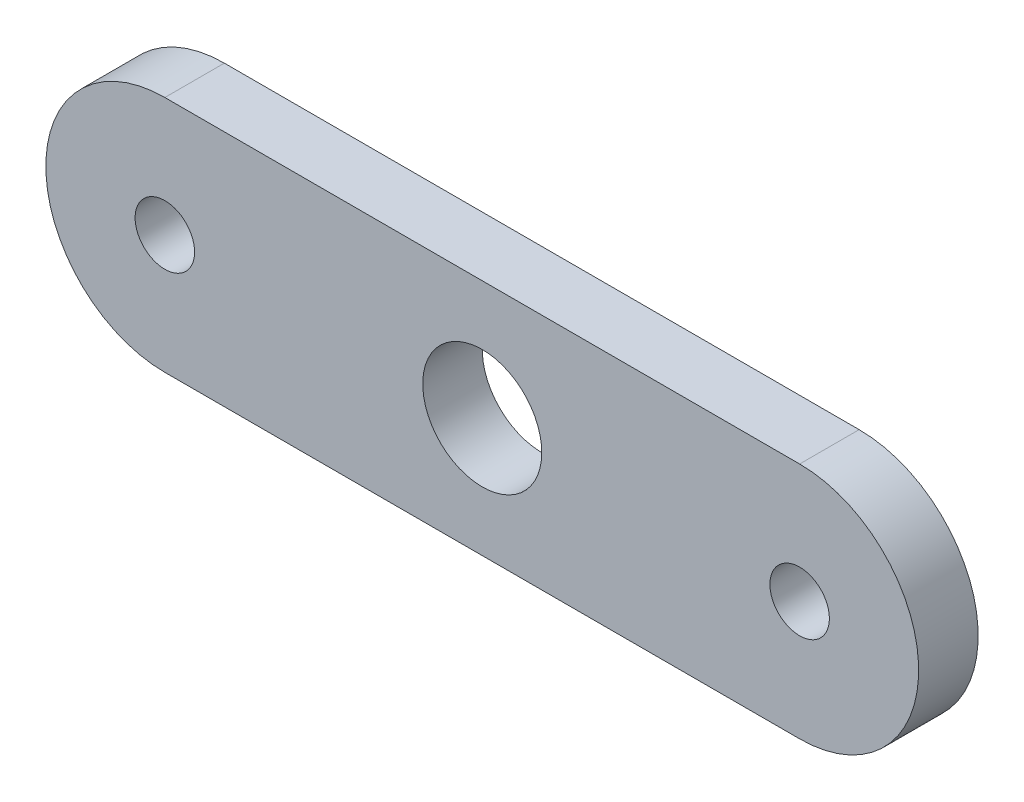
SolidWorks part; units mm, degrees
ref_plane "Front Plane" through (0, 0, 0) normal (0, 0, 1) x (1, 0, 0)
ref_plane "Top Plane" through (0, 0, 0) normal (0, 1, 0) x (1, 0, 0)
ref_plane "Right Plane" through (0, 0, 0) normal (1, 0, 0) x (0, 0, -1)
sketch "Sketch1" plane through (0, 0, 0) normal (0, 0, 1) x (1, 0, 0)
  line L0 (0, 0) -> (32, 0) construction
  line L1 (0, 6) -> (32, 6)
  line L2 (0, -6) -> (32, -6)
  arc A0 (0, 6) -> (0, -6) centre (0, 0) ccw
  arc A1 (32, -6) -> (32, 6) centre (32, 0) ccw
  circle A2 centre (0, 0) radius 1.5
  circle A3 centre (32, 0) radius 1.5
  circle A4 centre (16, 0) radius 3
  point P3 (16, 0)
  dimension "D1" = 6
  dimension "D2" = 3
  dimension "D3" = 32
  dimension "D4" = 12
extrude "Boss-Extrude1" add sketch "Sketch1" along normal blind 3
